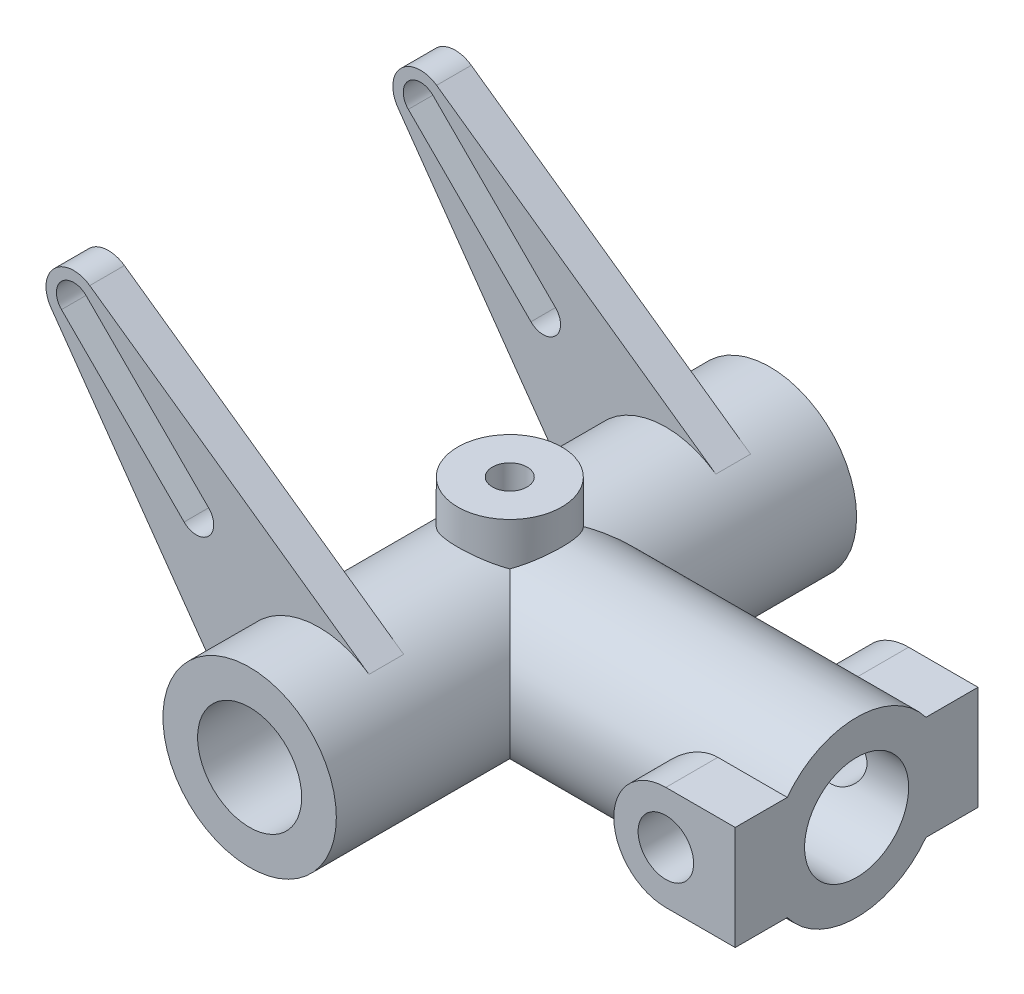
SolidWorks part; units mm, degrees
ref_plane "Alzado" through (0, 0, 0) normal (0, 0, 1) x (1, 0, 0)
ref_plane "Planta" through (0, 0, 0) normal (0, 1, 0) x (1, 0, 0)
ref_plane "Vista lateral" through (0, 0, 0) normal (1, 0, 0) x (0, 0, -1)
sketch "Croquis1" plane through (0, 0, 0) normal (0, 0, 1) x (1, 0, 0)
  circle A0 centre (0, 0) radius 25
  circle A1 centre (0, 0) radius 15
  dimension "D1" = 30
  dimension "D2" = 50
extrude "Saliente-Extruir1" add sketch "Croquis1" along normal blind 150
ref_plane "Plano1" through (0, 0, 120) normal (0, 0, 1) x (1, 0, 0)
sketch "Croquis2" plane through (0, 0, 120) normal (0, 0, 1) x (1, 0, 0)
  line L0 (0, 0) -> (-70.7107, 70.7107) construction
  line L1 (0, 0) -> (-39.7497, 0) construction
  line L3 (-70.7107, 70.7107) -> (-35.3553, 35.3553) construction
  line L4 (-67.1751, 74.2462) -> (-31.8198, 38.8909)
  line L5 (-74.2462, 67.1751) -> (-38.8909, 31.8198)
  line L6 (-77.2469, 66.0978) -> (-20.4256, -14.4152)
  line L7 (-66.0978, 77.2469) -> (14.4152, 20.4256)
  circle A0 centre (0, 0) radius 25 construction
  arc A1 (14.4152, 20.4256) -> (-20.4256, -14.4152) centre (0, 0) ccw
  arc A2 (-67.1751, 74.2462) -> (-74.2462, 67.1751) centre (-70.7107, 70.7107) ccw
  arc A3 (-38.8909, 31.8198) -> (-31.8198, 38.8909) centre (-35.3553, 35.3553) ccw
  arc A4 (-66.0978, 77.2469) -> (-77.2469, 66.0978) centre (-70.7107, 70.7107) ccw
  point P3 (-53.033, 53.033)
  dimension "D3" = 16
  dimension "D4" = 5
  dimension "D1" = 45
  dimension "D2" = 100
  dimension "D5" = 50
extrude "Saliente-Extruir2" add sketch "Croquis2" along normal blind 10
ref_plane "Plano2" through (0, 0, 30) normal (0, 0, -1) x (-1, 0, 0)
sketch "Croquis3" plane through (0, 0, 30) normal (0, 0, -1) x (-1, 0, 0)
  line L0 (77.2469, 66.0978) -> (20.4256, -14.4152) construction
  line L1 (74.2462, 67.1751) -> (38.8909, 31.8198) construction
  line L2 (31.8198, 38.8909) -> (67.1751, 74.2462) construction
  line L3 (-14.4152, 20.4256) -> (66.0978, 77.2469) construction
  line L4 (77.2469, 66.0978) -> (20.4256, -14.4152)
  line L5 (74.2462, 67.1751) -> (38.8909, 31.8198)
  line L6 (31.8198, 38.8909) -> (67.1751, 74.2462)
  line L7 (-14.4152, 20.4256) -> (66.0978, 77.2469)
  arc A0 (77.2469, 66.0978) -> (66.0978, 77.2469) centre (70.7107, 70.7107) ccw construction
  arc A1 (74.2462, 67.1751) -> (67.1751, 74.2462) centre (70.7107, 70.7107) ccw construction
  arc A2 (31.8198, 38.8909) -> (38.8909, 31.8198) centre (35.3553, 35.3553) ccw construction
  arc A3 (20.4256, -14.4152) -> (-14.4152, 20.4256) centre (0, 0) ccw construction
  arc A4 (77.2469, 66.0978) -> (66.0978, 77.2469) centre (70.7107, 70.7107) ccw
  arc A5 (74.2462, 67.1751) -> (67.1751, 74.2462) centre (70.7107, 70.7107) ccw
  arc A6 (31.8198, 38.8909) -> (38.8909, 31.8198) centre (35.3553, 35.3553) ccw
  arc A7 (20.4256, -14.4152) -> (-14.4152, 20.4256) centre (0, 0) ccw
extrude "Saliente-Extruir3" add sketch "Croquis3" along normal blind 10
ref_plane "Plano3" through (100, 0, 0) normal (1, 0, 0) x (0, 0, -1)
sketch "Croquis4" plane through (100, 0, 0) normal (1, 0, 0) x (0, 0, -1)
  line L0 (-150, 0) -> (0, 0) construction
  line L1 (-150, 25) -> (-150, -25) construction
  circle A0 centre (-75, 0) radius 25
  circle A1 centre (-75, 0) radius 15
  dimension "D1" = 30
  dimension "D2" = 50
extrude "Saliente-Extruir4" add sketch "Croquis4" against normal up to surface (75 mm away) up to face at (25, 0, 0)
ref_plane "Plano4" through (0, 0, 75) normal (0, 0, 1) x (1, 0, 0)
sketch "Croquis5" plane through (0, 0, 75) normal (0, 0, 1) x (1, 0, 0)
  line L0 (100, 0) -> (100, 15)
  line L3 (100, -25) -> (100, 25) construction
  line L4 (100, 15) -> (100, -15)
  line L5 (80, 15) -> (100, 15)
  line L6 (100, 15) -> (100.315, 14.7981)
  line L7 (80, -15) -> (100, -15)
  circle A0 centre (80, 0) radius 8
  arc A1 (80, 15) -> (80, -15) centre (80, 0) ccw
  dimension "D2" = 20
  dimension "D3" = 16
  dimension "D1" = 15
extrude "Saliente-Extruir5" add sketch "Croquis5" along normal mid plane 70 contours L5 A1 L7 L4 L0 A0
sketch "Croquis6" plane through (0, 0, 110) normal (0, 0, 1) x (1, 0, 0)
  circle A0 centre (80, 0) radius 8 construction
  circle A1 centre (80, 0) radius 8
extrude "Cortar-Extruir1" cut sketch "Croquis6" against normal through all
sketch "Croquis7" plane through (100, 0, 0) normal (1, 0, 0) x (0, 0, -1)
  circle A0 centre (-75, 0) radius 15
extrude "Cortar-Extruir2" cut sketch "Croquis7" against normal up to surface (85 mm away) up to face at (15, 0, 150)
ref_plane "Plano5" through (0, 35, 0) normal (0, 1, 0) x (1, 0, 0)
sketch "Croquis8" plane through (0, 35, 0) normal (0, 1, 0) x (1, 0, 0)
  line L0 (0, 0) -> (0, -150) construction
  line L1 (-25, -150) -> (25, -150) construction
  circle A0 centre (0, -75) radius 15
  circle A1 centre (0, -75) radius 5
  dimension "D1" = 10
  dimension "D2" = 30
extrude "Saliente-Extruir6" add sketch "Croquis8" against normal up to surface (10 mm away)
sketch "Croquis9" plane through (0, 35, 0) normal (0, 1, 0) x (1, 0, 0)
  circle A0 centre (0, -75) radius 5 construction
  circle A1 centre (0, -75) radius 5
extrude "Cortar-Extruir3" cut sketch "Croquis9" against normal up to surface (20 mm away)
